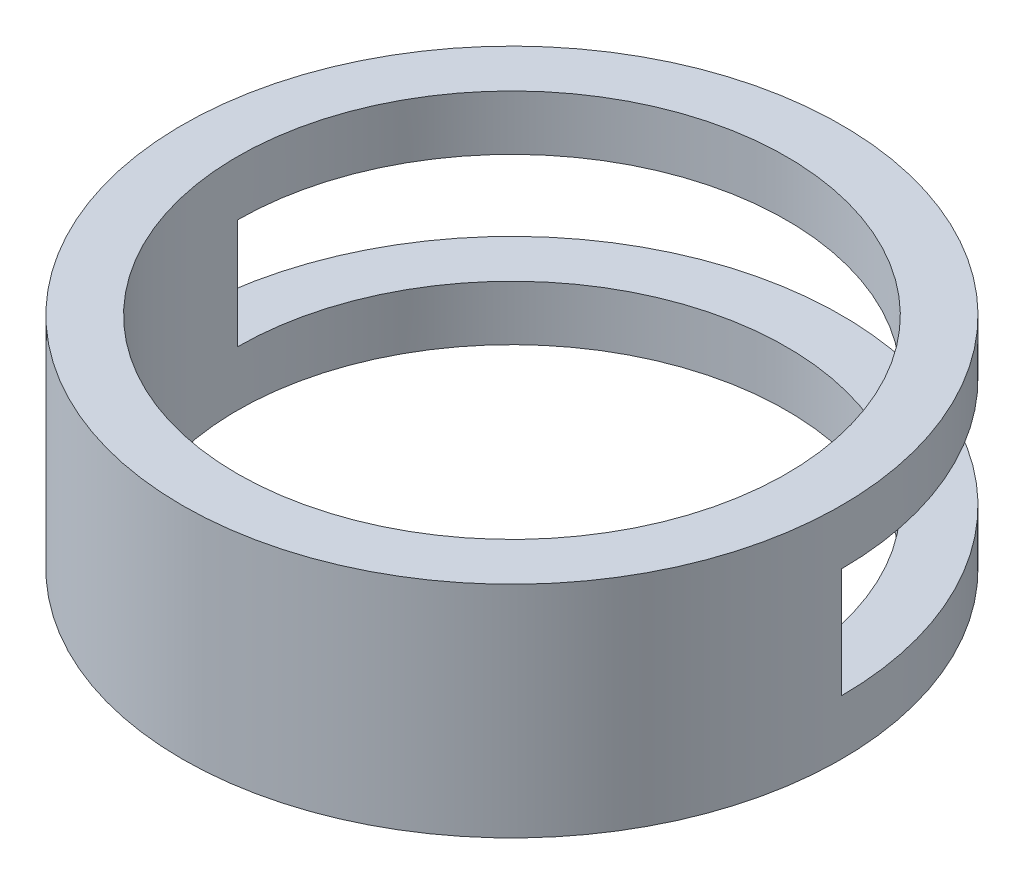
SolidWorks part; units mm, degrees
ref_plane "Front Plane" through (0, 0, 0) normal (0, 0, 1) x (1, 0, 0)
ref_plane "Top Plane" through (0, 0, 0) normal (0, 1, 0) x (1, 0, 0)
ref_plane "Right Plane" through (0, 0, 0) normal (1, 0, 0) x (0, 0, -1)
sketch "Sketch1" plane through (0, 0, 0) normal (0, 1, 0) x (1, 0, 0)
  line L0 (-34.9424, 0) -> (34.9424, 0) construction
  circle A0 centre (0, 0) radius 25
  circle A1 centre (0, 0) radius 30
  point P7 (0, 0)
  dimension "D1" = 60
  dimension "D2" = 50
extrude "Boss-Extrude1" add sketch "Sketch1" along normal mid plane 20
sketch "Sketch3" plane through (0, 0, 0) normal (0, 1, 0) x (1, 0, 0)
  line L0 (25, 0) -> (30, 0)
  line L1 (-25, 0) -> (-30, 0)
  circle A0 centre (0, 0) radius 30 construction
  circle A1 centre (0, 0) radius 25
  circle A2 centre (0, 0) radius 30
  point P6 (0, 0)
  dimension "D1" = 50
  dimension "D2" = 60
  dimension "D3" = 5
  dimension "D4" = 5
extrude "Cut-Extrude1" cut sketch "Sketch3" against normal mid plane 10 contours L0 A2 L1 A1
